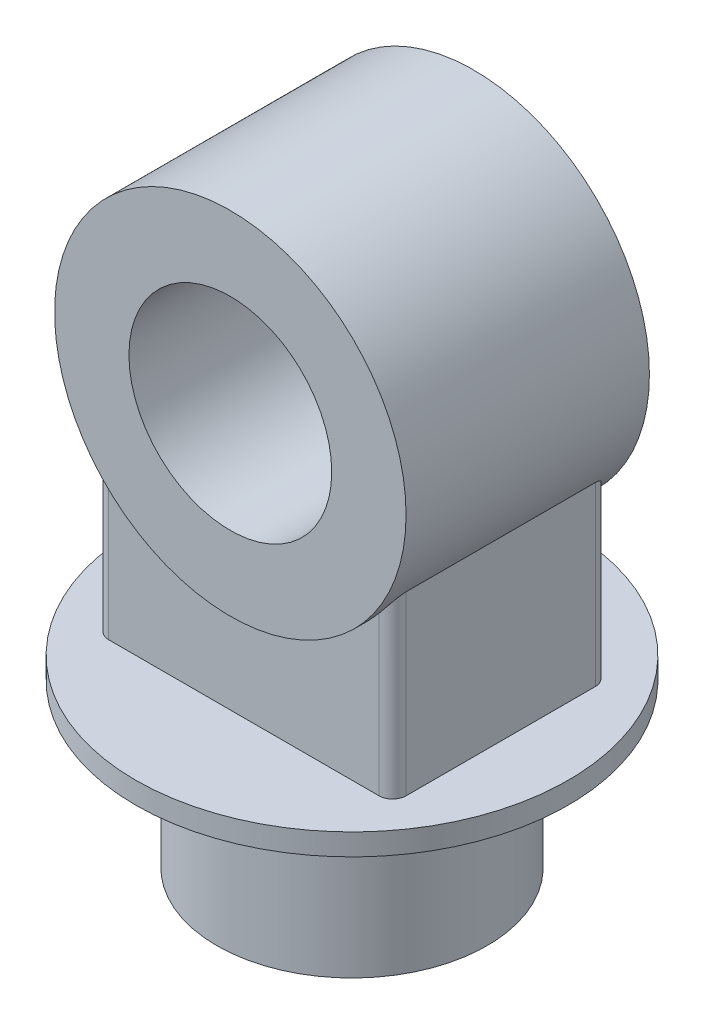
SolidWorks part; units mm, degrees
ref_plane "Front Plane" through (0, 0, 0) normal (0, 0, 1) x (1, 0, 0)
ref_plane "Top Plane" through (0, 0, 0) normal (0, 1, 0) x (1, 0, 0)
ref_plane "Right Plane" through (0, 0, 0) normal (1, 0, 0) x (0, 0, -1)
sketch "Sketch2" plane through (0, 0, 0) normal (0, 1, 0) x (1, 0, 0)
  circle A0 centre (0, 0) radius 100
  dimension "D1" = 200
extrude "Boss-Extrude1" add sketch "Sketch2" along normal blind 120
sketch "Sketch3" plane through (0, 120, 0) normal (0, 1, 0) x (1, 0, 0)
  circle A0 centre (0, 0) radius 160
  dimension "D1" = 320
extrude "Boss-Extrude2" add sketch "Sketch3" along normal blind 16
sketch "Sketch7" plane through (0, 0, 0) normal (0, 0, 1) x (1, 0, 0)
  line L0 (160, 136) -> (-160, 136) construction
  circle A0 centre (0, 336) radius 75
  circle A1 centre (0, 336) radius 130
  dimension "D1" = 150
  dimension "D2" = 260
  dimension "D3" = 200
extrude "Boss-Extrude3" add sketch "Sketch7" along normal mid plane 180 separate body
sketch "Sketch8" plane through (0, 136, 0) normal (0, 1, 0) x (1, 0, 0)
  line L1 (110, -80) -> (-110, -80)
  line L2 (110, -80) -> (110, 80)
  line L3 (110, 80) -> (-110, 80)
  line L4 (-110, -80) -> (-110, 80)
  line L5 (110, -80) -> (-110, 80) construction
  line L6 (110, 80) -> (-110, -80) construction
  point P0 (0, 0)
  dimension "D1" = 160
  dimension "D2" = 220
extrude "Boss-Extrude4" add sketch "Sketch8" along normal up to next
fillet "Fillet1" radius 10 4 edges at (110, 201.359, -80) (110, 201.359, 80) (-110, 201.359, -80) (-110, 201.359, 80)
